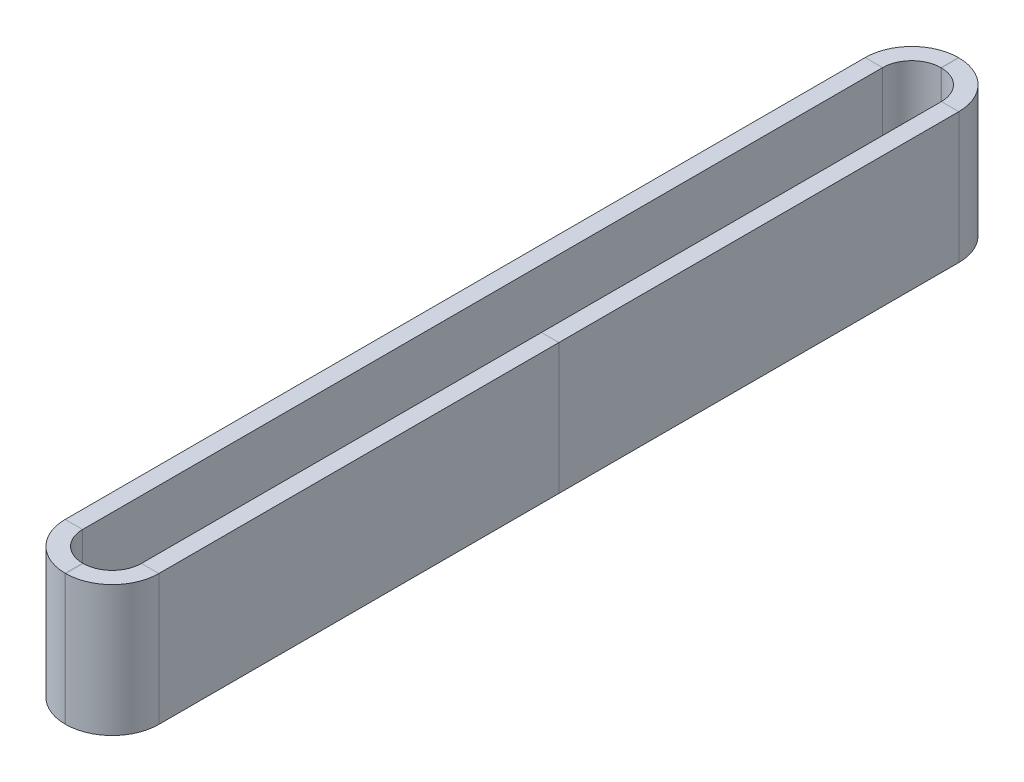
SolidWorks part; units mm, degrees
ref_plane "Ön Düzlem" through (0, 0, 0) normal (0, 0, 1) x (1, 0, 0)
ref_plane "Üst Düzlem" through (0, 0, 0) normal (0, 1, 0) x (1, 0, 0)
ref_plane "Sağ Düzlem" through (0, 0, 0) normal (1, 0, 0) x (0, 0, -1)
sketch "Sketch1" plane through (0, 0, 0) normal (0, 1, 0) x (1, 0, 0)
  line L1 (-0.05, 100.5) -> (0.05, 100.5)
  line L2 (-8.75, 91.8) -> (-8.75, -91.8)
  line L3 (-0.05, -100.5) -> (0.05, -100.5)
  line L4 (8.75, 91.8) -> (8.75, -91.8)
  line L5 (-8.75, 100.5) -> (8.75, -100.5) construction
  line L6 (-8.75, -100.5) -> (8.75, 100.5) construction
  arc A0 (-8.75, -91.8) -> (-0.05, -100.5) centre (-0.05, -91.8) ccw
  arc A1 (8.75, -91.8) -> (0.05, -100.5) centre (0.05, -91.8) cw
  arc A2 (0.05, 100.5) -> (8.75, 91.8) centre (0.05, 91.8) cw
  arc A3 (-0.05, 100.5) -> (-8.75, 91.8) centre (-0.05, 91.8) ccw
  point P0 (0, 0)
  dimension "D3" = 8.7
  dimension "D1" = 17.5
  dimension "D2" = 201
sketch "Sketch3" plane through (0, 0, 0) normal (0, 0, 1) x (1, 0, 0)
  line L0 (8.75, 0) -> (0.05, 0) construction
  line L1 (8.75, 0) -> (0.05, 0)
  line L3 (6.75, 15) -> (10.75, 15)
  line L4 (6.75, 15) -> (6.75, -15)
  line L5 (6.75, -15) -> (10.75, -15)
  line L6 (10.75, 15) -> (10.75, -15)
  line L7 (6.75, 15) -> (10.75, -15) construction
  line L8 (6.75, -15) -> (10.75, 15) construction
  dimension "D1" = 4
  dimension "D2" = 30
sweep "Sweep1" add profiles "Sketch3" path "Sketch1"
